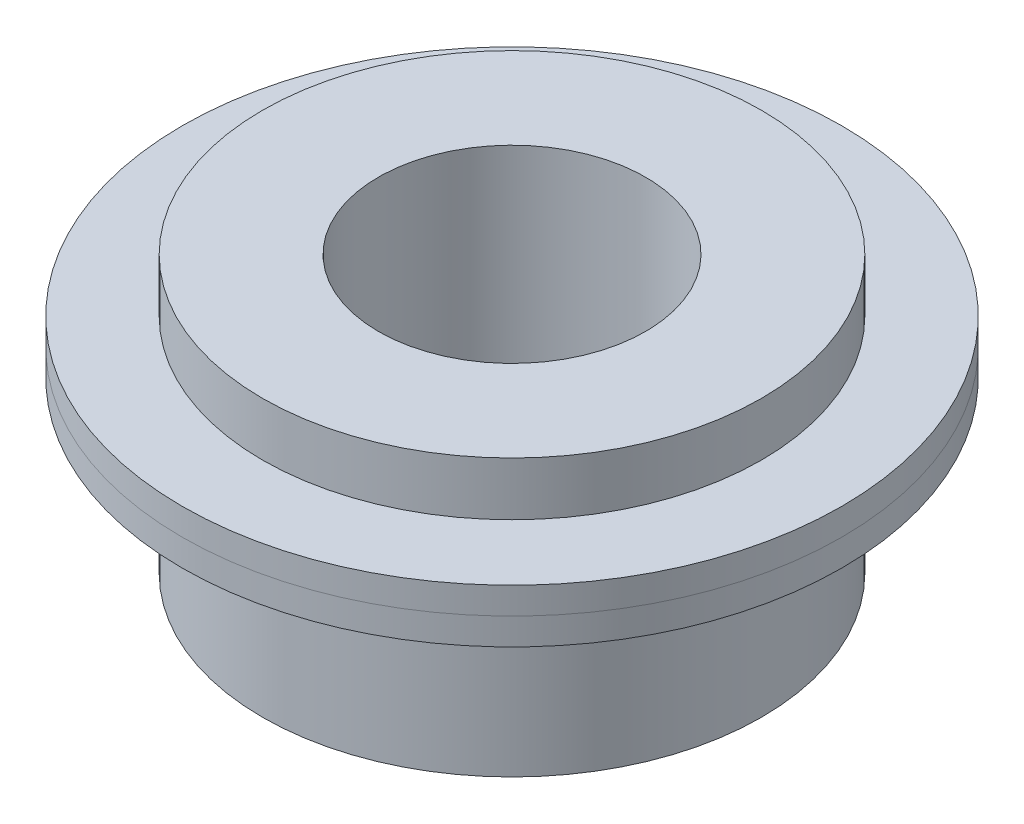
SolidWorks part; units mm, degrees
ref_plane "Front Plane" through (0, 0, 0) normal (0, 0, 1) x (1, 0, 0)
ref_plane "Top Plane" through (0, 0, 0) normal (0, 1, 0) x (1, 0, 0)
ref_plane "Right Plane" through (0, 0, 0) normal (1, 0, 0) x (0, 0, -1)
sketch "Sketch1" plane through (0, 0, 0) normal (0, 0, 1) x (1, 0, 0)
  line L0 (0, 7.4669) -> (0, -7.4338) construction
  line L1 (0, 4.553) -> (-7.5, 4.553) construction
  line L2 (-7.5, 4.553) -> (-14, 4.553)
  line L3 (-14, 4.553) -> (-14, 1.553)
  line L4 (-14, 1.553) -> (-18.5, 1.553)
  line L5 (-18.5, 1.553) -> (-18.5, 0.053)
  line L8 (-14, 0.053) -> (-18.5, 0.053)
  line L10 (-14, 0.053) -> (-14, -10.947)
  line L11 (-14, -10.947) -> (-7.5, -10.947)
  line L12 (-7.5, -10.947) -> (-7.5, 4.553)
  dimension "D1" = 7.5
  dimension "D2" = 6.5
  dimension "D3" = 4.5
  dimension "D4" = 3
  dimension "D5" = 1.5
  dimension "D6" = 11
revolve "Revolve1" add sketch "Sketch1" angle 360 about L0
sketch "Sketch2" plane through (0, 0.053, 0) normal (0, -1, 0) x (1, 0, 0)
  circle A1 centre (0, 0) radius 18.5
  circle A2 centre (0, 0) radius 18.5
  circle M2 centre (0, 0) radius 14
  circle M3 centre (0, 0) radius 18.5
  dimension "D1" = 0
extrude "Boss-Extrude1" add sketch "Sketch2" along normal blind 1.5 separate body contours M3 M2
